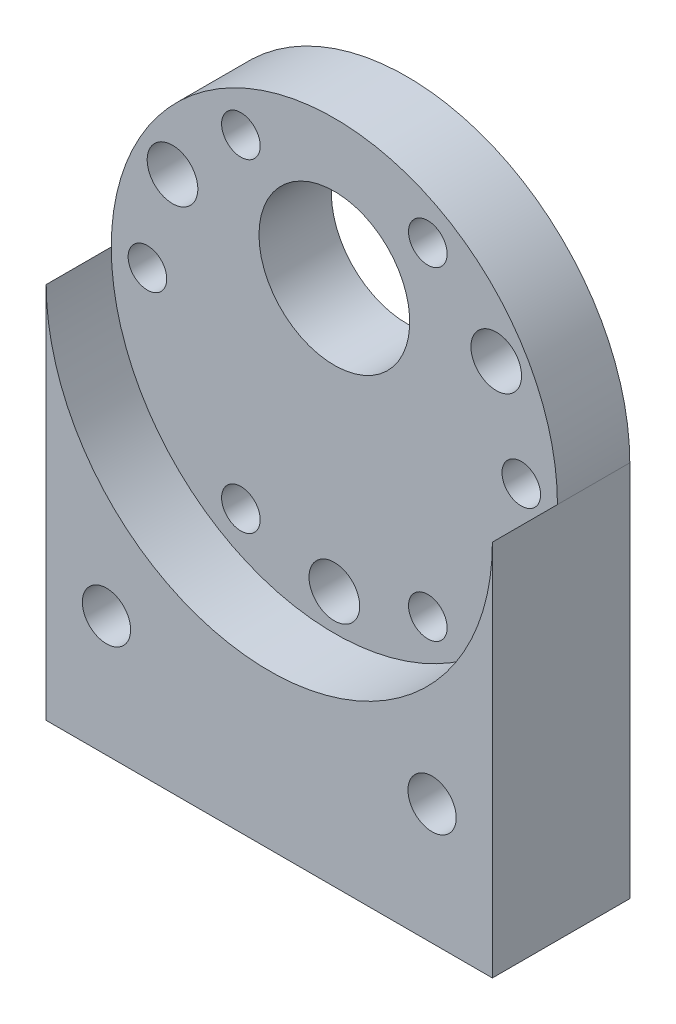
SolidWorks part; units mm, degrees
ref_plane "Front Plane" through (0, 0, 0) normal (0, 0, 1) x (1, 0, 0)
ref_plane "Top Plane" through (0, 0, 0) normal (0, 1, 0) x (1, 0, 0)
ref_plane "Right Plane" through (0, 0, 0) normal (1, 0, 0) x (0, 0, -1)
sketch "Sketch1" plane through (0, 0, 0) normal (0, 0, 1) x (1, 0, 0)
  circle A0 centre (0, 7) radius 6.25
  circle A1 centre (0, 7) radius 6.25 construction
  circle A2 centre (15.5, 0) radius 1.6
  circle A3 centre (0, 0) radius 18.5
  circle A4 centre (7.75, -13.4234) radius 1.6
  circle A5 centre (-7.75, -13.4234) radius 1.6
  circle A6 centre (-15.5, 0) radius 1.6
  circle A7 centre (-7.75, 13.4234) radius 1.6
  circle A8 centre (7.75, 13.4234) radius 1.6
  circle A9 centre (13.4234, 7.75) radius 2.1
  circle A10 centre (0, -15.5) radius 2.1
  circle A11 centre (-13.4234, 7.75) radius 2.1
  point P22 (0, 0)
  point P24 (0.0752, -15.4676)
  point P31 (0, 0)
  dimension "D1" = 3.2
  dimension "D3" = 37
  dimension "D4" = 3
  dimension "D5" = 4.2
  dimension "D6" = 15.5
  dimension "D2" = 6
extrude "Boss-Extrude1" add sketch "Sketch1" along normal up to surface (6 mm away)
sketch "Sketch3" plane through (0, 0, 6) normal (0, 0, 1) x (1, 0, 0)
  line L0 (-110, -6.301) -> (40, -6.301) construction
  line L1 (-18.5, 0) -> (18.5, 0) construction
  line L2 (-18.5, 0) -> (-18.5, -31.301)
  line L3 (-18.5, -31.301) -> (18.5, -31.301)
  line L4 (18.5, 0) -> (18.5, -31.301)
  line L5 (-18.5, 0) -> (18.5, -31.301) construction
  line L6 (-18.5, -31.301) -> (18.5, 0) construction
  line L7 (0, -31.301) -> (0, 0) construction
  circle A0 centre (0, 0) radius 18.5
  circle A1 centre (-13.5, -21.301) radius 2
  circle A2 centre (13.5, -21.301) radius 2
  point P7 (0, -15.6505)
  circle M16 centre (0, 0) radius 18.5
  dimension "D4" = 4
  dimension "D6" = 10
  dimension "D1" = 25
  dimension "D2" = 37
  dimension "D3" = 18.5
  dimension "D5" = 5
extrude "Boss-Extrude2" add sketch "Sketch3" along normal up to surface and the other way up to surface contours L4 L2 L3 A1 A2 M16
sketch "Sketch4" plane through (0, 0, 0) normal (0, 0, -1) x (-1, 0, 0)
  circle A0 centre (-13.5, -21.301) radius 3.5
  circle A1 centre (13.5, -21.301) radius 3.5
  dimension "D1" = 7
  dimension "D2" = 7
extrude "Cut-Extrude1" cut sketch "Sketch4" against normal blind 5
